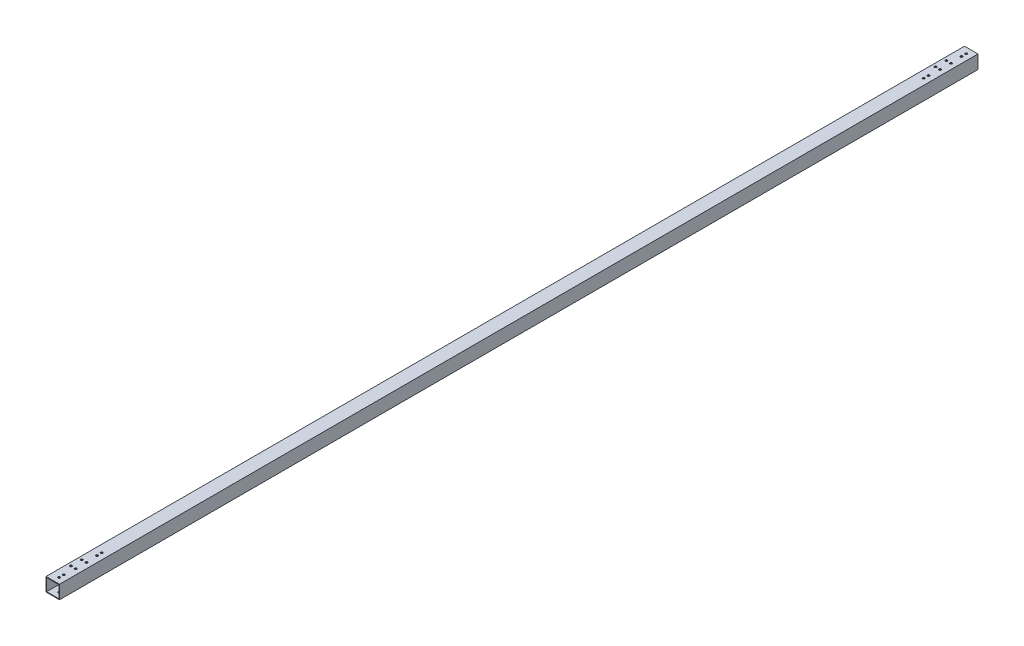
SolidWorks part; units mm, degrees
material "1100-H18 棒材(SS)"
ref_plane "前视基准面" through (0, 0, 0) normal (0, 0, 1) x (1, 0, 0)
ref_plane "上视基准面" through (0, 0, 0) normal (0, 1, 0) x (1, 0, 0)
ref_plane "右视基准面" through (0, 0, 0) normal (1, 0, 0) x (0, 0, -1)
other "Configuration Table"
sketch "草图1" plane through (0, 0, 0) normal (0, 0, 1) x (1, 0, 0)
  line L1 (0, 0) -> (20, 0)
  line L2 (0, 0) -> (0, 20)
  line L3 (0, 20) -> (20, 20)
  line L4 (20, 0) -> (20, 20)
  line L5 (1, 1) -> (19, 1)
  line L6 (1, 1) -> (1, 19)
  line L7 (1, 19) -> (19, 19)
  line L8 (19, 1) -> (19, 19)
  dimension "D1" = 20
  dimension "D2" = 20
  dimension "D3" = 1
  dimension "D4" = 1
  dimension "D5" = 1
  dimension "D6" = 1
extrude "凸台-拉伸1" add sketch "草图1" along normal blind 1360
sketch "草图2" plane through (0, 20, 0) normal (0, 1, 0) x (1, 0, 0)
  circle A1 centre (11, -15.5) radius 1.6
  circle A2 centre (11, -15.5) radius 1.6
  circle A3 centre (11, -8.5) radius 1.6
  circle A4 centre (11, -8.5) radius 1.6
  circle A5 centre (11, -71.5) radius 1.6
  circle A6 centre (11, -71.5) radius 1.6
  circle A7 centre (11, -64.5) radius 1.6
  circle A8 centre (11, -64.5) radius 1.6
  circle A9 centre (11, -1295.5) radius 1.6
  circle A10 centre (11, -1295.5) radius 1.6
  circle A11 centre (11, -1288.5) radius 1.6
  circle A12 centre (11, -1288.5) radius 1.6
  circle A13 centre (11, -1351.5) radius 1.6
  circle A14 centre (11, -1351.5) radius 1.6
  circle A15 centre (11, -1344.5) radius 1.6
  circle A16 centre (11, -1344.5) radius 1.6
  dimension "D1" = 0
  dimension "D2" = 0
  dimension "D3" = 0
  dimension "D4" = 0
  dimension "D5" = 0
  dimension "D6" = 0
  dimension "D7" = 0
  dimension "D8" = 0
extrude "切除-拉伸1" cut sketch "草图2" against normal through all
sketch "草图3" plane through (0, 0, 0) normal (0, -1, 0) x (1, 0, 0)
  circle A1 centre (12, 1312) radius 1.6
  circle A2 centre (12, 1312) radius 1.6
  circle A3 centre (12, 1328) radius 1.6
  circle A4 centre (12, 1328) radius 1.6
  circle A5 centre (12, 32) radius 1.6
  circle A7 centre (12, 32) radius 1.6
  circle A9 centre (12, 48) radius 1.6
  circle A11 centre (12, 48) radius 1.6
  circle A13 centre (5, 1312) radius 1.6
  circle A14 centre (5, 1312) radius 1.6
  circle A15 centre (5, 1328) radius 1.6
  circle A16 centre (5, 1328) radius 1.6
  circle A25 centre (5, 32) radius 1.6
  circle A26 centre (5, 32) radius 1.6
  circle A27 centre (5, 48) radius 1.6
  circle A28 centre (5, 48) radius 1.6
  dimension "D1" = 0
  dimension "D2" = 0
  dimension "D3" = 0
  dimension "D4" = 0
  dimension "D7" = 0
  dimension "D8" = 0
  dimension "D11" = 0
  dimension "D12" = 0
extrude "切除-拉伸2" cut sketch "草图3" against normal through all
